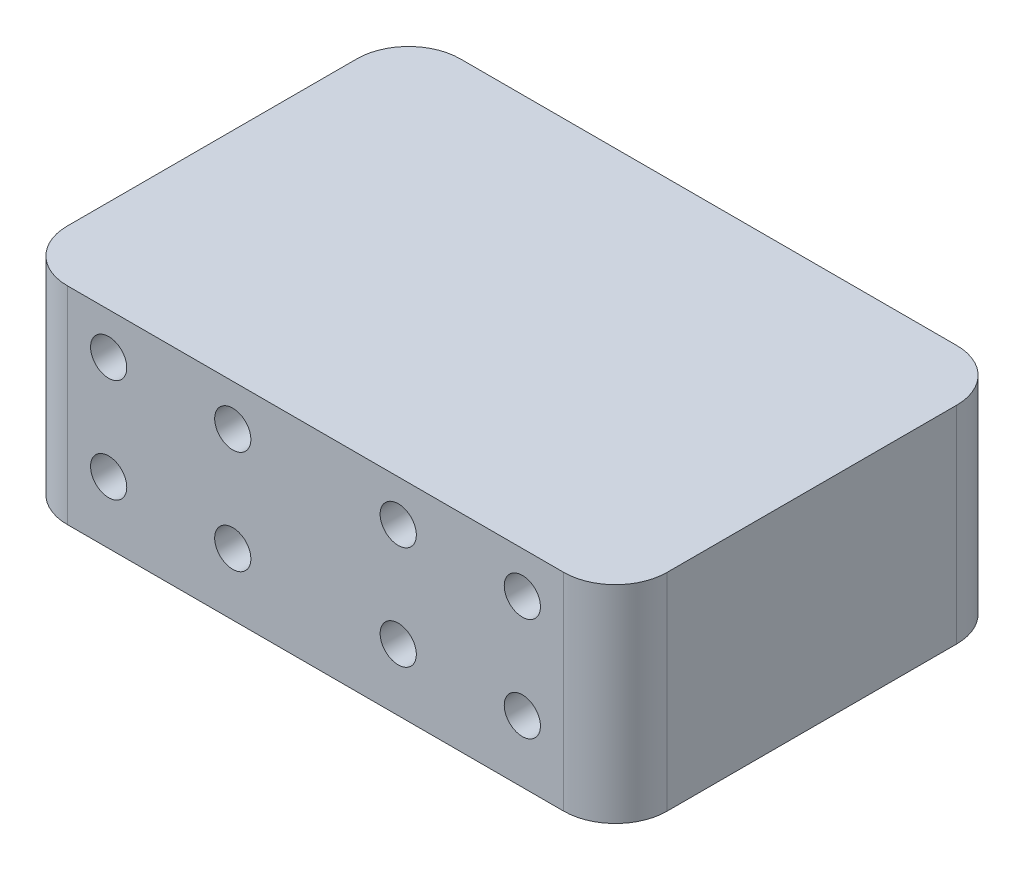
SolidWorks part; units mm, degrees
material "PVC 0.007 Plasticized 塑化聚氯乙烯"
ref_plane "前视基准面" through (0, 0, 0) normal (0, 0, 1) x (1, 0, 0)
ref_plane "上视基准面" through (0, 0, 0) normal (0, 1, 0) x (1, 0, 0)
ref_plane "右视基准面" through (0, 0, 0) normal (1, 0, 0) x (0, 0, -1)
other "Configuration Table"
sketch "草图1" plane through (0, 0, 0) normal (0, 0, 1) x (1, 0, 0)
  line L0 (29, -4) -> (-29, -4) construction
  line L1 (-29, -10) -> (29, -10)
  line L2 (-29, -10) -> (-29, 10)
  line L3 (-29, 10) -> (29, 10)
  line L4 (29, -10) -> (29, 10)
  line L5 (-29, -10) -> (29, 10) construction
  line L6 (-29, 10) -> (29, -10) construction
  line L7 (-29, 6) -> (29, 6) construction
  line L8 (0, 0) -> (0, 10) construction
  line L9 (-20, 6) -> (-20, -4) construction
  circle A0 centre (-20, 6) radius 1.75
  circle A1 centre (-8, 6) radius 1.75
  circle A2 centre (8, 6) radius 1.75
  circle A3 centre (20, 6) radius 1.75
  circle A4 centre (-20, -4) radius 1.75
  circle A5 centre (-8, -4) radius 1.75
  circle A6 centre (8, -4) radius 1.75
  circle A7 centre (20, -4) radius 1.75
  point P0 (0, 0)
  dimension "D5" = 9
  dimension "D6" = 12
  dimension "D7" = 3.5
  dimension "D1" = 58
  dimension "D2" = 20
  dimension "D3" = 6
  dimension "D4" = 10
  dimension "D9" = 10
  dimension "D8" = 2
extrude "凸台-拉伸1" add sketch "草图1" along normal blind 38
fillet "圆角1" radius 5 4 edges at (-29, 0, 0) (-29, 0, 38) (29, 0, 0) (29, 0, 38)
sketch "草图4" plane through (0, 0, 38) normal (0, 0, 1) x (1, 0, 0)
  circle A0 centre (-20, 6) radius 3.5
  circle A1 centre (-8, 6) radius 3.5
  circle A2 centre (8, 6) radius 3.5
  circle A3 centre (20, 6) radius 3.5
  circle A4 centre (20, -4) radius 3.5
  circle A5 centre (8, -4) radius 3.5
  circle A6 centre (-8, -4) radius 3.5
  circle A7 centre (-20, -4) radius 3.5
  dimension "D1" = 7
